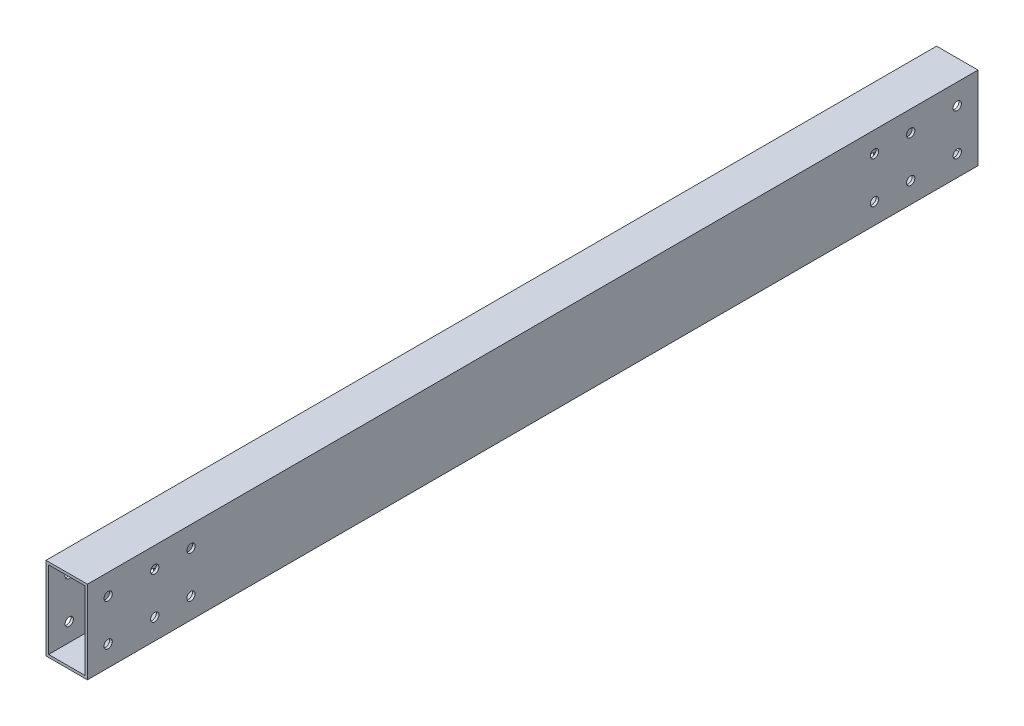
SolidWorks part; units mm, degrees
ref_plane "Front Plane" through (0, 0, 0) normal (0, 0, 1) x (1, 0, 0)
ref_plane "Top Plane" through (0, 0, 0) normal (0, 1, 0) x (1, 0, 0)
ref_plane "Right Plane" through (0, 0, 0) normal (1, 0, 0) x (0, 0, -1)
sketch "Sketch1" plane through (0, 0, 0) normal (0, 0, 1) x (1, 0, 0)
  line L1 (0, 0) -> (25.4, 0)
  line L2 (0, 0) -> (0, 50.8)
  line L3 (0, 50.8) -> (25.4, 50.8)
  line L4 (25.4, 0) -> (25.4, 50.8)
  line L5 (1.5875, 1.5875) -> (23.8125, 1.5875)
  line L6 (1.5875, 1.5875) -> (1.5875, 49.2125)
  line L7 (1.5875, 49.2125) -> (23.8125, 49.2125)
  line L8 (23.8125, 1.5875) -> (23.8125, 49.2125)
  dimension "D1" = 25.4
  dimension "D2" = 50.8
  dimension "D3" = 1.5875
  dimension "D4" = 1.5875
  dimension "D5" = 1.5875
  dimension ".0625" = 1.5875
extrude "Boss-Extrude1" add sketch "Sketch1" along normal blind 546.1
sketch "Sketch2" plane through (25.4, 0, 0) normal (1, 0, 0) x (0, 0, -1)
  line L0 (-546.1, 0) -> (-546.1, 50.8) construction
  line L1 (-546.1, 50.8) -> (0, 50.8) construction
  line L2 (-546.1, 0) -> (0, 0) construction
  line L4 (-273.05, 50.8) -> (-273.05, 0) construction
  circle A0 centre (-504.825, 38.1) radius 2.54
  circle A1 centre (-504.825, 12.7) radius 2.54
  circle A4 centre (-482.6, 38.1) radius 2.54
  circle A5 centre (-482.6, 12.7) radius 2.54
  circle A30 centre (-533.4, 12.7) radius 2.54
  circle A36 centre (-533.4, 38.1) radius 2.54
  circle A37 centre (-12.7, 38.1) radius 2.54
  circle A38 centre (-12.7, 12.7) radius 2.54
  circle A39 centre (-63.5, 12.7) radius 2.54
  circle A40 centre (-63.5, 38.1) radius 2.54
  circle A41 centre (-41.275, 12.7) radius 2.54
  circle A42 centre (-41.275, 38.1) radius 2.54
  dimension "D1" = 5.08
  dimension "D2" = 22.225
  dimension ".625" = 41.275
  dimension "D3" = 12.7
  dimension "D4" = 12.7
  dimension "D6" = 12.7
extrude "Cut-Extrude1" cut sketch "Sketch2" against normal through all
